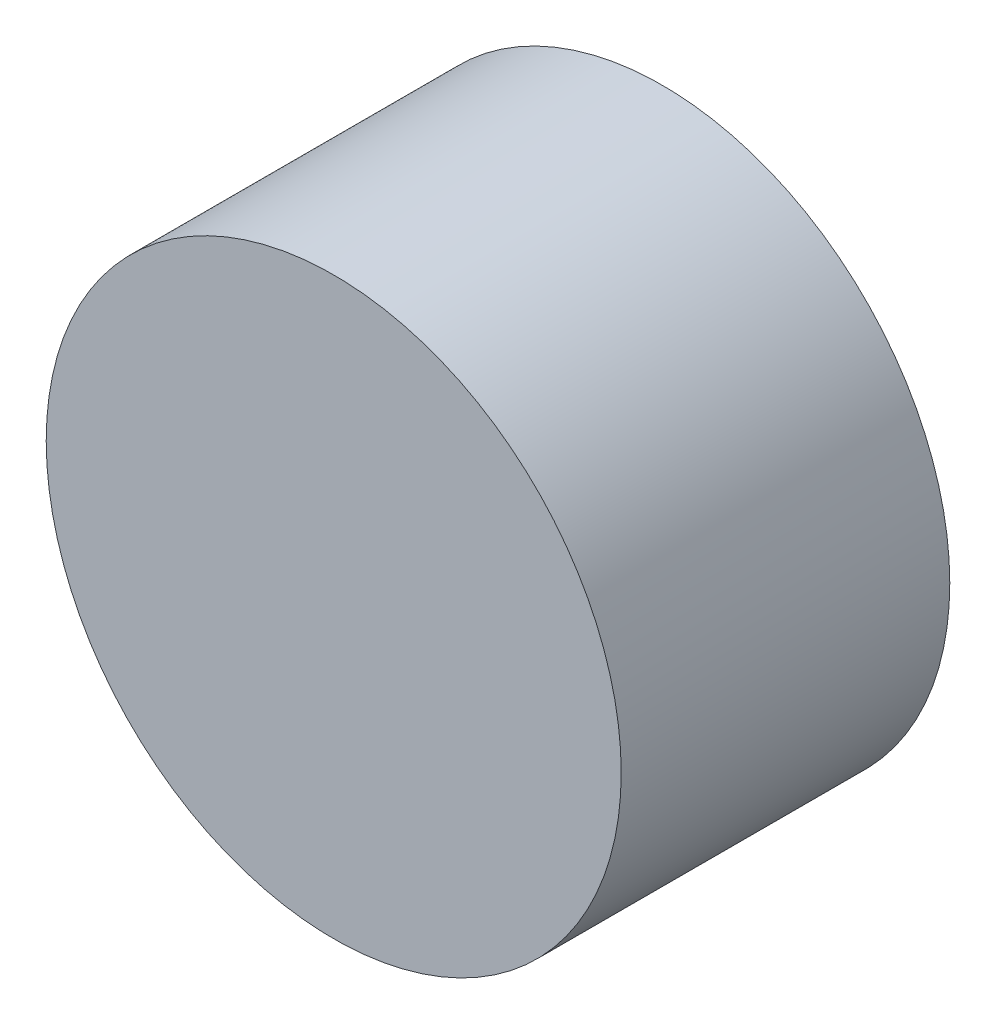
SolidWorks part; units mm, degrees
material "Q235A"
ref_plane "前视" through (0, 0, 0) normal (0, 0, 1) x (1, 0, 0)
ref_plane "上视" through (0, 0, 0) normal (0, 1, 0) x (1, 0, 0)
ref_plane "右视" through (0, 0, 0) normal (1, 0, 0) x (0, 0, -1)
sketch "草图1" plane through (0, 0, 0) normal (0, 0, 1) x (1, 0, 0)
  circle A0 centre (0, 0) radius 17.5
  dimension "D1" = 35
extrude "凸台-拉伸1" add sketch "草图1" along normal blind 20
